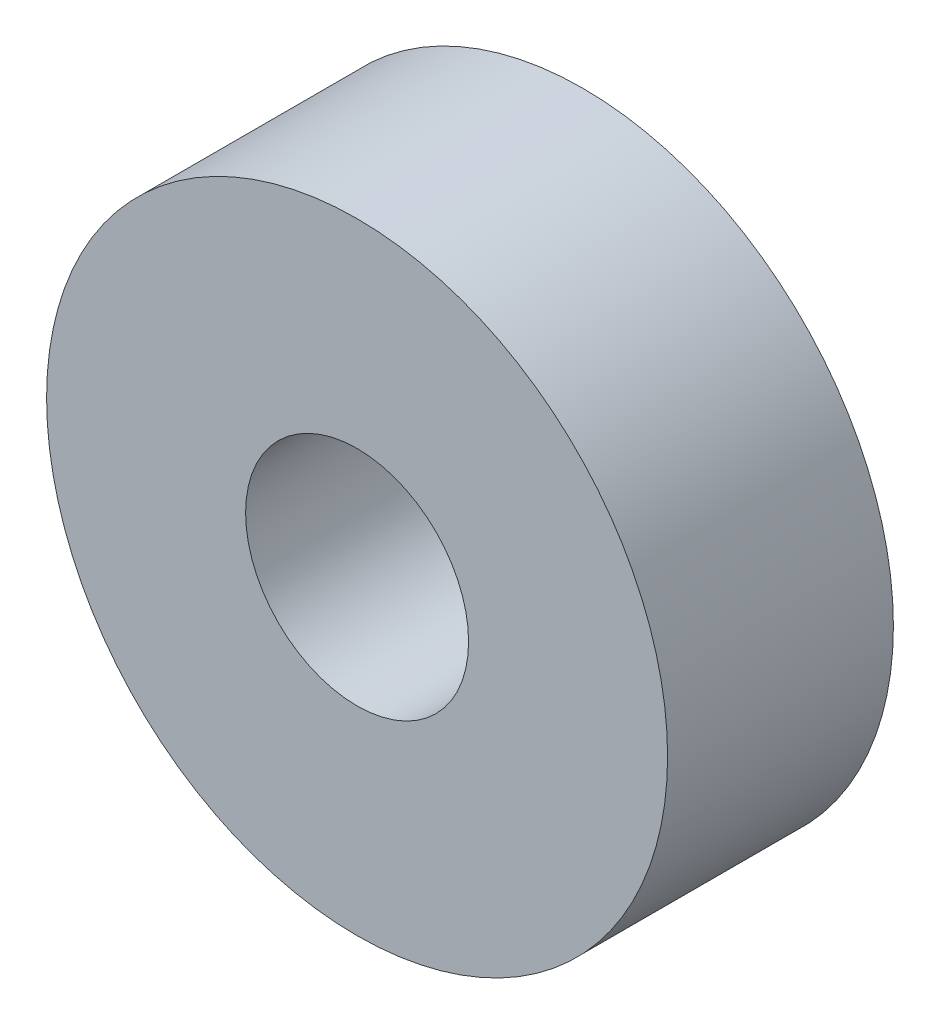
SolidWorks part; units mm, degrees
ref_plane "Front Plane" through (0, 0, 0) normal (0, 0, 1) x (1, 0, 0)
ref_plane "Top Plane" through (0, 0, 0) normal (0, 1, 0) x (1, 0, 0)
ref_plane "Right Plane" through (0, 0, 0) normal (1, 0, 0) x (0, 0, -1)
sketch "Sketch1" plane through (0, 0, 0) normal (0, 0, 1) x (1, 0, 0)
  circle A0 centre (0, 0) radius 11
  circle A1 centre (0, 0) radius 3.95
  dimension "D1" = 7.9
  dimension "D2" = 22
extrude "Boss-Extrude1" add sketch "Sketch1" along normal blind 8
